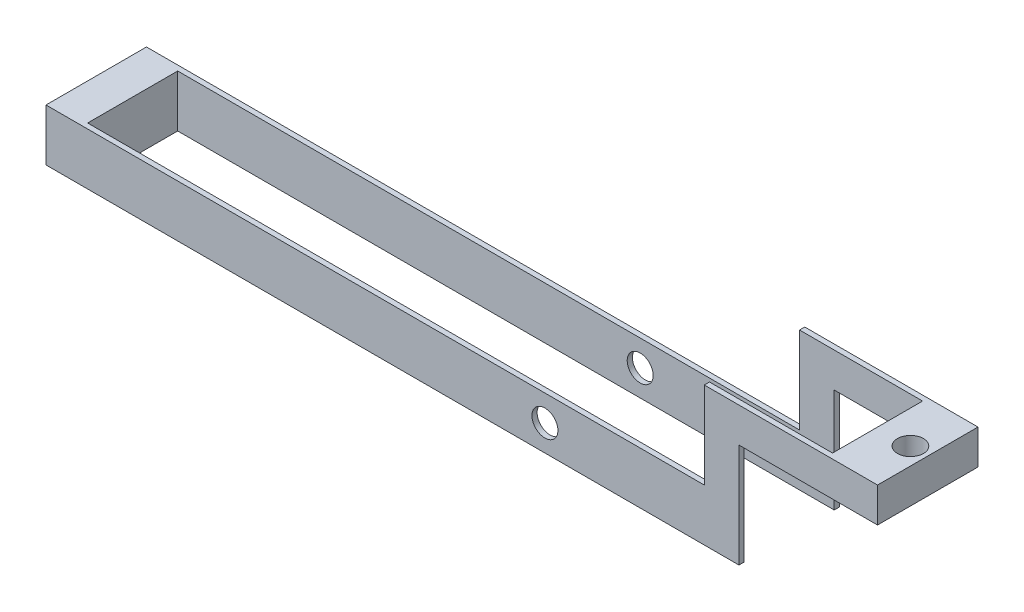
SolidWorks part; units mm, degrees
ref_plane "Front Plane" through (0, 0, 0) normal (0, 0, 1) x (1, 0, 0)
ref_plane "Top Plane" through (0, 0, 0) normal (0, 1, 0) x (1, 0, 0)
ref_plane "Right Plane" through (0, 0, 0) normal (1, 0, 0) x (0, 0, -1)
sketch "Sketch1" plane through (0, 0, 0) normal (0, 0, 1) x (1, 0, 0)
  line L0 (254, 38.1) -> (254, 0)
  line L1 (0, 0) -> (254, 0)
  line L2 (0, 0) -> (0, 19.05)
  line L3 (0, 19.05) -> (241.3, 19.05)
  line L7 (304.8, 50.8) -> (241.3, 50.8)
  line L8 (241.3, 19.05) -> (241.3, 50.8)
  line L9 (241.3, 50.8) -> (304.8, 50.8)
  line L10 (241.3, 50.8) -> (241.3, 19.05)
  line L11 (254, 38.1) -> (304.8, 38.1)
  line L12 (304.8, 50.8) -> (304.8, 38.1)
  line L14 (304.8, 50.8) -> (304.8, 38.1)
  circle A0 centre (182.88, 9.525) radius 4.7625
  dimension "D4" = 9.525
  dimension "D1" = 19.05
  dimension "D2" = 254
  dimension "D3" = 241.3
  dimension "D5" = 12.7
  dimension "D6" = 63.5
  dimension "D7" = 38.1
  dimension "D8" = 9.525
  dimension "D9" = 182.88
extrude "Boss-Extrude1" add sketch "Sketch1" along normal blind 36.83 contours L12 L7 L8 L3 L2 L1 L0 L11 A0
sketch "Sketch2" plane through (0, 0, 0) normal (0, -1, 0) x (1, 0, 0)
  line L0 (0, 18.415) -> (254, 18.415) construction
  line L1 (13.3511, 34.925) -> (286.4011, 34.925)
  line L2 (13.3511, 34.925) -> (13.3511, 1.905)
  line L3 (13.3511, 1.905) -> (286.4011, 1.905)
  line L4 (286.4011, 34.925) -> (286.4011, 1.905)
  line L5 (0, 36.83) -> (0, 0) construction
  line L6 (254, 36.83) -> (254, 0) construction
  point P10 (13.3511, 18.415)
  dimension "D1" = 33.02
  dimension "D2" = 273.05
extrude "Cut-Extrude1" cut sketch "Sketch2" against normal through all
sketch "Sketch4" plane through (0, 50.8, 0) normal (0, 1, 0) x (1, 0, 0)
  line L0 (304.8, -36.83) -> (304.8, 0) construction
  circle A0 centre (298.45, -18.415) radius 4.7625
  point P4 (304.8, -18.415)
  dimension "D1" = 9.525
  dimension "D2" = 6.35
extrude "Cut-Extrude3" cut sketch "Sketch4" against normal through all
